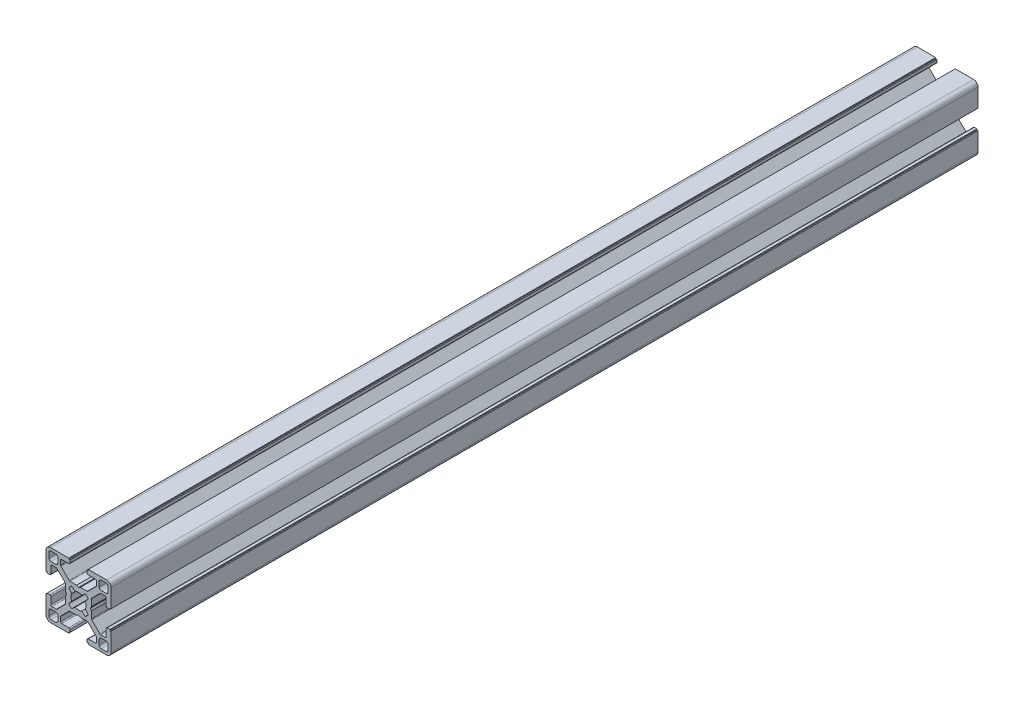
SolidWorks part; units mm, degrees
ref_plane "Front Plane" through (0, 0, 0) normal (0, 0, 1) x (1, 0, 0)
ref_plane "Top Plane" through (0, 0, 0) normal (0, 1, 0) x (1, 0, 0)
ref_plane "Right Plane" through (0, 0, 0) normal (1, 0, 0) x (0, 0, -1)
sketch "Sketch1" plane through (0, 0, 0) normal (0, 0, 1) x (1, 0, 0)
  line L0 (-15, 0) -> (15, 0) construction
  line L1 (0, -15) -> (0, 15) construction
  line L2 (-4.5, 15) -> (4.5, 15) construction
  line L3 (-4, -15) -> (4, -15) construction
  line L4 (-4.5, 15) -> (-4.5, 14.5)
  line L5 (-4.5, 14.5) -> (-4, 14.5)
  line L6 (-4, 14.5) -> (-4, 13.29)
  line L7 (-4.5, 12.79) -> (-7.7675, 12.79)
  line L8 (-8.2675, 12.29) -> (-8.2675, 10.2707)
  line L9 (-8.1211, 9.9171) -> (-4.3504, 6.1464)
  line L10 (-3.9968, 6) -> (0, 6)
  line L11 (0, 0) -> (-15, 15) construction
  line L12 (-4.5, 15) -> (-12.968, 15)
  line L14 (-12.705, 9.5135) -> (-10.5135, 9.5135)
  line L15 (-13.705, 10.5135) -> (-13.705, 12.705)
  line L16 (-12.705, 13.705) -> (-10.5135, 13.705)
  line L17 (-9.5135, 10.5135) -> (-9.5135, 12.705)
  line L18 (-13.705, 9.5135) -> (-9.5135, 13.705) construction
  line L19 (-13.705, 13.705) -> (-9.5135, 9.5135) construction
  line L20 (-3.1568, 4.5038) -> (-1.5303, 3.1477) construction
  line L21 (-4.5038, 3.1568) -> (-3.1477, 1.5303) construction
  line L22 (-6, 3.9968) -> (-6, 0)
  line L23 (-9.9171, 8.1211) -> (-6.1464, 4.3504)
  line L24 (-15, 4.5) -> (-15, 12.968)
  line L25 (-12.29, 8.2675) -> (-10.2707, 8.2675)
  line L26 (-12.79, 4.5) -> (-12.79, 7.7675)
  line L27 (-14.5, 4) -> (-13.29, 4)
  line L28 (-14.5, 4.5) -> (-14.5, 4)
  line L29 (-15, 4.5) -> (-14.5, 4.5)
  circle A0 centre (0, 0) radius 3.5
  arc A1 (-12.968, 15) -> (-15, 12.968) centre (-12.968, 12.968) ccw
  circle A2 centre (0, 0) radius 5.5 construction
  arc A3 (-10.5135, 9.5135) -> (-9.5135, 10.5135) centre (-10.5135, 10.5135) ccw
  arc A4 (-13.705, 12.705) -> (-12.705, 13.705) centre (-12.705, 12.705) cw
  arc A5 (-10.5135, 13.705) -> (-9.5135, 12.705) centre (-10.5135, 12.705) cw
  arc A6 (-12.705, 9.5135) -> (-13.705, 10.5135) centre (-12.705, 10.5135) cw
  arc A7 (-12.79, 4.5) -> (-13.29, 4) centre (-13.29, 4.5) cw
  arc A8 (-12.29, 8.2675) -> (-12.79, 7.7675) centre (-12.29, 7.7675) ccw
  arc A9 (-9.9171, 8.1211) -> (-10.2707, 8.2675) centre (-10.2707, 7.7675) ccw
  arc A10 (-6, 3.9968) -> (-6.1464, 4.3504) centre (-6.5, 3.9968) ccw
  arc A11 (-4.3504, 6.1464) -> (-3.9968, 6) centre (-3.9968, 6.5) ccw
  arc A12 (-4, 13.29) -> (-4.5, 12.79) centre (-4.5, 13.29) cw
  arc A13 (-7.7675, 12.79) -> (-8.2675, 12.29) centre (-7.7675, 12.29) ccw
  arc A14 (-8.2675, 10.2707) -> (-8.1211, 9.9171) centre (-7.7675, 10.2707) ccw
  point P4 (0, 0)
  point P8 (0, 0)
  point P13 (0, 15)
  point P15 (0, -15)
  point P16 (0, 6)
  point P23 (-11.6092, 11.6093)
  point P26 (0, 6)
  point P62 (-12.79, 4)
  point P65 (-12.79, 8.2675)
  point P68 (-10.0636, 8.2675)
  point P71 (-6, 4.2039)
  point P74 (-4.2039, 6)
  point P77 (-4, 12.79)
  point P80 (-8.2675, 12.79)
  point P83 (-8.2675, 10.0636)
  dimension "Center Hole Diameter" = 7
  dimension "D11" = 2.032
  dimension "D9" = 11
  dimension "D13" = 1
  dimension "D14" = 0.5
  dimension "Rail Height" = 30
  dimension "Rail Width" = 30
  dimension "T-Slot Width" = 8
  dimension "T-Slot Depth" = 9
  dimension "D1" = 9
  dimension "D2" = 45
  dimension "D3" = 8
  dimension "D4" = 2.21
  dimension "D5" = 16.535
  dimension "D7" = 2.54
  dimension "D6" = 1.295
  dimension "D8" = 1.246
  dimension "D10" = 10.36
  dimension "D12" = 1.905
sketch "Sketch2" plane through (0, 0, 0) normal (1, 0, 0) x (0, 0, -1)
  line L0 (-76.2, 0) -> (76.2, 0) construction
  line L2 (0, -15) -> (0, 15) construction
  line L3 (0, -15) -> (0, 15) construction
  line L4 (-76.2, -15) -> (-76.2, 15) construction
  line L5 (76.2, -15) -> (76.2, 15) construction
  point P0 (-38.7, 0)
  point P3 (0, 0)
  point P4 (38.7, 0)
  point P12 (-76.2, 0)
  point P14 (76.2, 0)
  dimension "Length" = 152.4
  dimension "D1" = 37.5
sketch "Sketch3" plane through (0, 0, 0) normal (0, 0, 1) x (1, 0, 0)
  line L0 (-4.5038, 3.1568) -> (-3.1477, 1.5303)
  line L1 (0, 3.5) -> (0, 5.5)
  line L2 (-5.5, 0) -> (-3.5, 0)
  line L7 (-6, 3.9968) -> (-6, 0) construction
  line L31 (-9.9171, 8.1211) -> (-6.1464, 4.3504) construction
  line L117 (-12.29, 8.2675) -> (-10.2707, 8.2675) construction
  line L118 (-12.79, 4.5) -> (-12.79, 7.7675) construction
  line L157 (-12.705, 9.5135) -> (-10.5135, 9.5135)
  line L158 (-9.5135, 10.5135) -> (-9.5135, 12.705)
  line L163 (-10.5135, 13.705) -> (-12.705, 13.705)
  line L164 (-13.705, 12.705) -> (-13.705, 10.5135)
  line L165 (-12.705, 9.5135) -> (-10.5135, 9.5135)
  line L166 (-9.5135, 10.5135) -> (-9.5135, 12.705)
  line L167 (-10.5135, 13.705) -> (-12.705, 13.705)
  line L168 (-13.705, 12.705) -> (-13.705, 10.5135)
  line L169 (-14.5, 4) -> (-13.29, 4) construction
  line L170 (-14.5, 4.5) -> (-14.5, 4) construction
  line L171 (-15, 4.5) -> (-14.5, 4.5) construction
  line L172 (-15, 4.5) -> (-15, 12.968) construction
  line L173 (-4.5, 15) -> (-12.968, 15) construction
  line L174 (-4.5, 15) -> (-4.5, 14.5) construction
  line L175 (-4.5, 14.5) -> (-4, 14.5) construction
  line L176 (-4, 14.5) -> (-4, 13.29) construction
  line L177 (-4.5, 12.79) -> (-7.7675, 12.79) construction
  line L178 (-8.2675, 12.29) -> (-8.2675, 10.2707) construction
  line L179 (-8.1211, 9.9171) -> (-4.3504, 6.1464) construction
  line L180 (-3.9968, 6) -> (0, 6) construction
  line L181 (-6, 3.9968) -> (-6, 0.866)
  line L182 (-9.9171, 8.1211) -> (-6.1464, 4.3504)
  line L183 (-12.29, 8.2675) -> (-10.2707, 8.2675)
  line L184 (-12.79, 4.5) -> (-12.79, 7.7675)
  line L185 (-14.5, 4) -> (-13.29, 4)
  line L186 (-14.5, 4.5) -> (-14.5, 4)
  line L187 (-15, 4.5) -> (-14.5, 4.5)
  line L188 (-15, 4.5) -> (-15, 12.968)
  line L189 (-4.5, 15) -> (-12.968, 15)
  line L190 (-4.5, 15) -> (-4.5, 14.5)
  line L191 (-4.5, 14.5) -> (-4, 14.5)
  line L192 (-4, 14.5) -> (-4, 13.29)
  line L193 (-4.5, 12.79) -> (-7.7675, 12.79)
  line L194 (-8.2675, 12.29) -> (-8.2675, 10.2707)
  line L195 (-8.1211, 9.9171) -> (-4.3504, 6.1464)
  line L196 (-3.9968, 6) -> (-0.866, 6)
  line L197 (-0.866, 6) -> (0, 5.5)
  line L198 (0, -15) -> (0, 15) construction
  line L199 (0, 0) -> (-15, 15) construction
  line L200 (0, 0) -> (-15, 15) construction
  line L201 (-3.1568, 4.5038) -> (-1.5303, 3.1477) construction
  line L202 (-3.1568, 4.5038) -> (-1.5303, 3.1477)
  line L203 (-6, 0.866) -> (-5.5, 0)
  line L204 (-15, 0) -> (15, 0) construction
  line L205 (-15, 0) -> (15, 0) construction
  line L206 (0, -15) -> (0, 15) construction
  arc A0 (-3.5, 0) -> (-3.1477, 1.5303) centre (0, 0) cw
  arc A10 (-6, 3.9968) -> (-6.1464, 4.3504) centre (-6.5, 3.9968) ccw construction
  circle A16 centre (0, 0) radius 3.5
  arc A18 (0, 3.5) -> (-1.5303, 3.1477) centre (0, 0) ccw
  arc A20 (-9.9171, 8.1211) -> (-10.2707, 8.2675) centre (-10.2707, 7.7675) ccw construction
  arc A22 (-12.29, 8.2675) -> (-12.79, 7.7675) centre (-12.29, 7.7675) ccw construction
  arc A28 (-13.29, 4) -> (-12.79, 4.5) centre (-13.29, 4.5) ccw construction
  arc A29 (-10.5135, 9.5135) -> (-9.5135, 10.5135) centre (-10.5135, 10.5135) ccw
  arc A30 (-9.5135, 12.705) -> (-10.5135, 13.705) centre (-10.5135, 12.705) ccw
  arc A31 (-12.705, 13.705) -> (-13.705, 12.705) centre (-12.705, 12.705) ccw
  arc A32 (-13.705, 10.5135) -> (-12.705, 9.5135) centre (-12.705, 10.5135) ccw
  arc A33 (-10.5135, 9.5135) -> (-9.5135, 10.5135) centre (-10.5135, 10.5135) ccw
  arc A34 (-9.5135, 12.705) -> (-10.5135, 13.705) centre (-10.5135, 12.705) ccw
  arc A35 (-12.705, 13.705) -> (-13.705, 12.705) centre (-12.705, 12.705) ccw
  arc A36 (-13.705, 10.5135) -> (-12.705, 9.5135) centre (-12.705, 10.5135) ccw
  arc A37 (-12.968, 15) -> (-15, 12.968) centre (-12.968, 12.968) ccw construction
  arc A38 (-4.5, 12.79) -> (-4, 13.29) centre (-4.5, 13.29) ccw construction
  arc A39 (-7.7675, 12.79) -> (-8.2675, 12.29) centre (-7.7675, 12.29) ccw construction
  arc A40 (-8.2675, 10.2707) -> (-8.1211, 9.9171) centre (-7.7675, 10.2707) ccw construction
  arc A41 (-4.3504, 6.1464) -> (-3.9968, 6) centre (-3.9968, 6.5) ccw construction
  arc A42 (-6, 3.9968) -> (-6.1464, 4.3504) centre (-6.5, 3.9968) ccw
  arc A43 (-9.9171, 8.1211) -> (-10.2707, 8.2675) centre (-10.2707, 7.7675) ccw
  arc A44 (-12.29, 8.2675) -> (-12.79, 7.7675) centre (-12.29, 7.7675) ccw
  arc A45 (-13.29, 4) -> (-12.79, 4.5) centre (-13.29, 4.5) ccw
  arc A46 (-12.968, 15) -> (-15, 12.968) centre (-12.968, 12.968) ccw
  arc A47 (-4.5, 12.79) -> (-4, 13.29) centre (-4.5, 13.29) ccw
  arc A48 (-7.7675, 12.79) -> (-8.2675, 12.29) centre (-7.7675, 12.29) ccw
  arc A49 (-8.2675, 10.2707) -> (-8.1211, 9.9171) centre (-7.7675, 10.2707) ccw
  arc A50 (-4.3504, 6.1464) -> (-3.9968, 6) centre (-3.9968, 6.5) ccw
  circle A51 centre (0, 0) radius 5.5 construction
  arc A52 (-3.1568, 4.5038) -> (-4.5038, 3.1568) centre (0, 0) ccw
  dimension "D3" = 60
  dimension "D4" = 60
  dimension "D1" = 0
  dimension "D2" = 0
extrude "Boss-Extrude1" add sketch "Sketch3" along normal mid plane 400
pattern_circular "CirPattern1" count 4 over 360 about axis through (0, 0, 0) along (0, 0, 1) of "Boss-Extrude1"
ref_plane "Contact Plane1" through (15, 0, 0) normal (1, 0, 0) x (0, 0, -1)
ref_plane "Contact Plane2" through (0, -15, 0) normal (0, 1, 0) x (1, 0, 0)
ref_plane "Contact Plane3" through (-15, 0, 0) normal (1, 0, 0) x (0, 0, -1)
ref_plane "Contact Plane4" through (0, 15, 0) normal (0, 1, 0) x (1, 0, 0)
equation "\"D1@Sketch2\" = \"Rail Height@Sketch1\" * 1.25"
equation "\"D1@Sketch1\"=\"T-Slot Width@Sketch1\"+1mm"
equation "\"D3@Sketch1\"=\"T-Slot Width@Sketch1\""
equation "\"D1@Boss-Extrude1\"=\"length\""
equation "\"length\"= 400mm"
